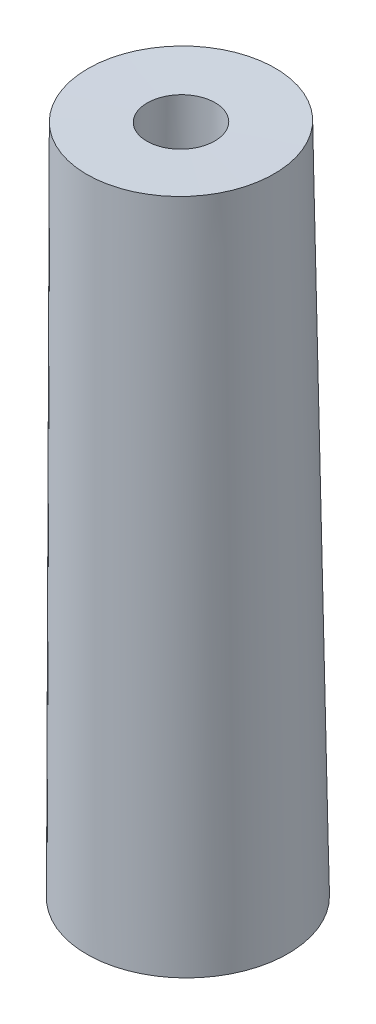
SolidWorks part; units mm, degrees
ref_plane "Front Plane" through (0, 0, 0) normal (0, 0, 1) x (1, 0, 0)
ref_plane "Top Plane" through (0, 0, 0) normal (0, 1, 0) x (1, 0, 0)
ref_plane "Right Plane" through (0, 0, 0) normal (1, 0, 0) x (0, 0, -1)
sketch "Sketch1" plane through (0, 0, 0) normal (0, 0, 1) x (1, 0, 0)
  line L0 (0, 49.6529) -> (0, -62.9322)
  line L4 (5.687, 49.6529) -> (6.8578, -62.9322) construction
revolve "Revolve-Thin1" add sketch "Sketch1" angle 360 about L4
